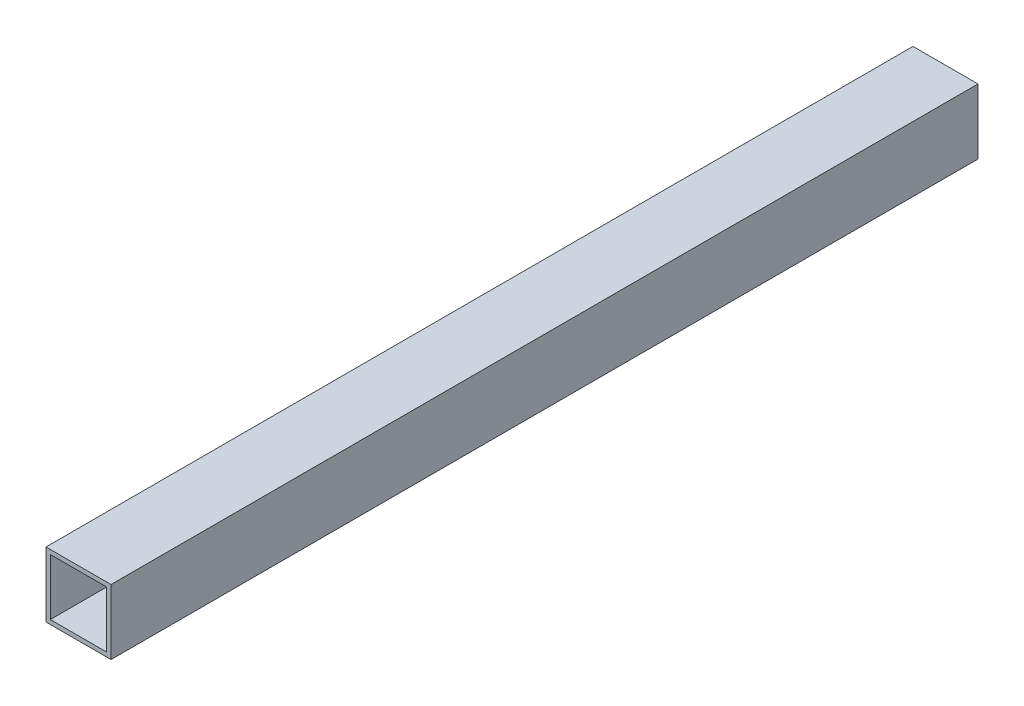
SolidWorks part; units mm, degrees
material "1060 合金"
ref_plane "前视基准面" through (0, 0, 0) normal (0, 0, 1) x (1, 0, 0)
ref_plane "上视基准面" through (0, 0, 0) normal (0, 1, 0) x (1, 0, 0)
ref_plane "右视基准面" through (0, 0, 0) normal (1, 0, 0) x (0, 0, -1)
other "Configuration Table"
sketch "草图1" plane through (0, 0, 0) normal (0, 0, 1) x (1, 0, 0)
  line L1 (0, 0) -> (15, 0)
  line L2 (0, 0) -> (0, -15)
  line L3 (0, -15) -> (15, -15)
  line L4 (15, 0) -> (15, -15)
  dimension "D1" = 15
  dimension "D2" = 15
extrude "拉伸-薄壁1" add sketch "草图1" along normal blind 200 thin
sketch "草图2" plane through (0, -15, 0) normal (0, -1, 0) x (1, 0, 0)
  circle A1 centre (7.5, 825) radius 2.6
  circle A2 centre (7.5, 825) radius 2.6
  dimension "D1" = 0
extrude "切除-拉伸1" [suppressed] cut sketch "草图2" against normal up to next
